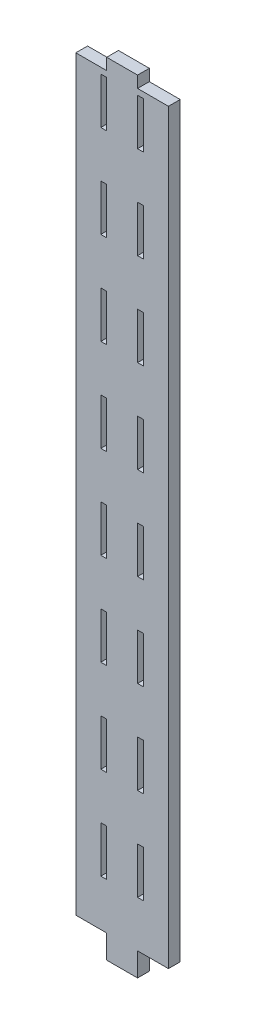
SolidWorks part; units mm, degrees
ref_plane "Front Plane" through (0, 0, 0) normal (0, 0, 1) x (1, 0, 0)
ref_plane "Top Plane" through (0, 0, 0) normal (0, 1, 0) x (1, 0, 0)
ref_plane "Right Plane" through (0, 0, 0) normal (1, 0, 0) x (0, 0, -1)
sketch "Sketch1" plane through (0, 0, 0) normal (0, 0, 1) x (1, 0, 0)
  line L2 (0, 0) -> (0, 403.175)
  line L3 (0, 403.175) -> (16.6667, 403.175)
  line L4 (50, 0) -> (50, 403.175)
  line L6 (16.6667, -12.7) -> (16.6667, 0)
  line L8 (33.3333, 0) -> (33.3333, -12.7)
  line L11 (16.6667, 0) -> (16.6667, 25) construction
  line L12 (33.3333, 150) -> (36.5033, 150)
  line L13 (33.3333, 150) -> (33.3333, 125)
  line L14 (33.3333, 50) -> (36.5083, 50)
  line L15 (33.3333, 50) -> (33.3333, 25)
  line L16 (33.3333, 25) -> (36.5083, 25)
  line L17 (36.5083, 50) -> (36.5083, 25)
  line L18 (16.6667, 50) -> (13.4917, 50)
  line L20 (16.6667, 25) -> (13.4917, 25)
  line L21 (13.4917, 50) -> (13.4917, 25)
  line L22 (33.3333, 100) -> (36.5033, 100)
  line L23 (33.3333, 100) -> (33.3333, 75)
  line L24 (33.3333, 75) -> (36.5033, 75)
  line L25 (36.5033, 100) -> (36.5033, 75)
  line L26 (16.6667, 100) -> (13.4917, 100)
  line L30 (33.3333, 0) -> (33.3333, 25) construction
  line L31 (33.3333, 125) -> (36.5033, 125)
  line L32 (36.5033, 150) -> (36.5033, 125)
  line L33 (16.6667, 150) -> (13.4917, 150)
  line L34 (16.6667, 150) -> (16.6667, 125)
  line L35 (16.6667, 125) -> (13.4917, 125)
  line L36 (13.4917, 150) -> (13.4917, 125)
  line L37 (33.3333, 200) -> (36.5033, 200)
  line L38 (33.3333, 200) -> (33.3333, 175)
  line L39 (33.3333, 175) -> (36.5033, 175)
  line L40 (36.5033, 200) -> (36.5033, 175)
  line L41 (16.6667, 200) -> (13.4917, 200)
  line L42 (16.6667, 200) -> (16.6667, 175)
  line L43 (16.6667, 175) -> (13.4917, 175)
  line L44 (13.4917, 200) -> (13.4917, 175)
  line L45 (33.3333, 250) -> (36.5033, 250)
  line L46 (33.3333, 250) -> (33.3333, 225)
  line L47 (33.3333, 225) -> (36.5033, 225)
  line L48 (36.5033, 250) -> (36.5033, 225)
  line L49 (16.6667, 250) -> (13.4917, 250)
  line L50 (16.6667, 250) -> (16.6667, 225)
  line L51 (16.6667, 225) -> (13.4917, 225)
  line L52 (13.4917, 250) -> (13.4917, 225)
  line L53 (33.3333, 300) -> (36.5033, 300)
  line L54 (33.3333, 300) -> (33.3333, 275)
  line L55 (33.3333, 275) -> (36.5033, 275)
  line L56 (36.5033, 300) -> (36.5033, 275)
  line L57 (16.6667, 300) -> (13.4917, 300)
  line L58 (16.6667, 300) -> (16.6667, 275)
  line L59 (16.6667, 275) -> (13.4917, 275)
  line L60 (13.4917, 300) -> (13.4917, 275)
  line L61 (33.3333, 350) -> (36.5033, 350)
  line L62 (33.3333, 350) -> (33.3333, 325)
  line L63 (33.3333, 325) -> (36.5033, 325)
  line L64 (36.5033, 350) -> (36.5033, 325)
  line L65 (16.6667, 350) -> (13.4917, 350)
  line L66 (16.6667, 350) -> (16.6667, 325)
  line L67 (16.6667, 325) -> (13.4917, 325)
  line L68 (13.4917, 350) -> (13.4917, 325)
  line L69 (33.3333, 400) -> (36.5033, 400)
  line L70 (33.3333, 400) -> (33.3333, 375)
  line L71 (33.3333, 375) -> (36.5033, 375)
  line L72 (36.5033, 400) -> (36.5033, 375)
  line L73 (16.6667, 400) -> (13.4917, 400)
  line L74 (16.6667, 400) -> (16.6667, 375)
  line L75 (16.6667, 375) -> (13.4917, 375)
  line L76 (13.4917, 400) -> (13.4917, 375)
  line L77 (16.6667, 50) -> (16.6667, 25)
  line L78 (33.3333, 50) -> (33.3333, 75) construction
  line L79 (33.3333, 100) -> (33.3333, 125) construction
  line L80 (16.6667, 100) -> (16.6667, 125) construction
  line L81 (33.3333, 150) -> (33.3333, 175) construction
  line L82 (16.6667, 150) -> (16.6667, 175) construction
  line L83 (16.6667, 200) -> (16.6667, 225) construction
  line L84 (33.3333, 200) -> (33.3333, 225) construction
  line L85 (16.6667, 250) -> (16.6667, 275) construction
  line L86 (33.3333, 250) -> (33.3333, 275) construction
  line L87 (16.6667, 300) -> (16.6667, 325) construction
  line L88 (33.3333, 300) -> (33.3333, 325) construction
  line L89 (33.3333, 350) -> (33.3333, 375) construction
  line L90 (16.6667, 350) -> (16.6667, 375) construction
  line L91 (13.4917, 100) -> (13.4917, 75)
  line L92 (13.4917, 75) -> (16.6667, 75)
  line L93 (16.6667, 75) -> (16.6667, 100)
  line L94 (16.6667, 75) -> (16.6667, 50) construction
  line L95 (33.3333, 403.175) -> (33.3333, 409.425)
  line L96 (33.3333, 409.425) -> (16.6667, 409.425)
  line L97 (16.6667, 409.425) -> (16.6667, 403.175)
  line L98 (33.3333, 403.175) -> (50, 403.175)
  line L99 (16.6667, -12.7) -> (33.3333, -12.7)
  line L100 (33.3333, 0) -> (50, 0)
  line L101 (16.6667, 0) -> (0, 0)
  dimension "D1" = 403.175
  dimension "D2" = 50
  dimension "D3" = 12.7
  dimension "D4" = 3.175
  dimension "D5" = 3.17
  dimension "D6" = 3.175
  dimension "D7" = 3.175
  dimension "D8" = 3.175
  dimension "D9" = 3.17
  dimension "D10" = 3.175
  dimension "D11" = 3.17
  dimension "D12" = 3.175
  dimension "D13" = 3.17
  dimension "D14" = 3.175
  dimension "D15" = 3.17
  dimension "D16" = 3.175
  dimension "D17" = 3.17
  dimension "D18" = 3.175
  dimension "D19" = 3.17
  dimension "D20" = 25
  dimension "D21" = 6.25
extrude "Boss-Extrude1" add sketch "Sketch1" along normal blind 6.35
